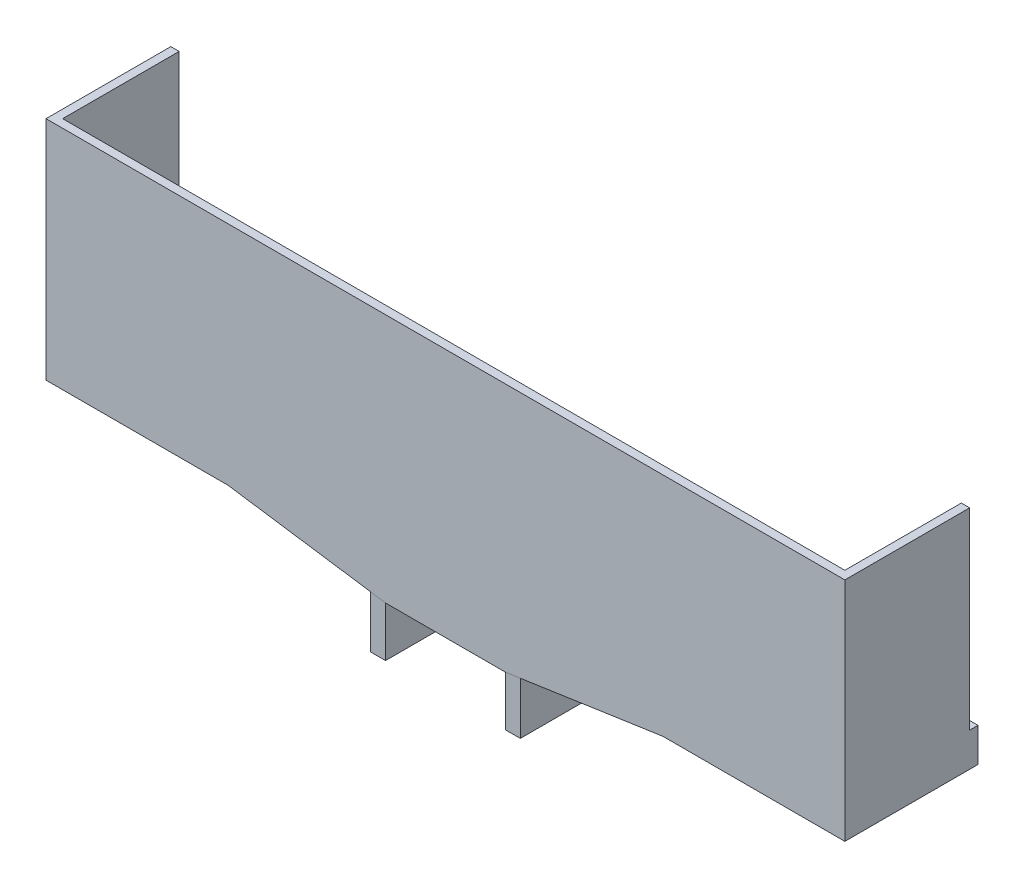
SolidWorks part; units mm, degrees
ref_plane "前基準面" through (0, 0, 0) normal (0, 0, 1) x (1, 0, 0)
ref_plane "上基準面" through (0, 0, 0) normal (0, 1, 0) x (1, 0, 0)
ref_plane "右基準面" through (0, 0, 0) normal (1, 0, 0) x (0, 0, -1)
sketch "草圖20" plane through (0, 0, 0) normal (0, 0, 1) x (1, 0, 0)
  line L0 (-36, 0) -> (36, 0) construction
  line L1 (-36, 0) -> (-240, 30)
  line L2 (-240, 30) -> (240, 30) construction
  line L3 (240, 30) -> (36, 0)
  line L4 (36, 0) -> (-36, 0)
  line L5 (0, 89.4424) -> (0, -40.7257) construction
  line L7 (-240, 30) -> (240, 30) construction
  line L8 (-240, 30) -> (-240, 150)
  line L9 (-240, 150) -> (240, 150)
  line L10 (240, 30) -> (240, 150)
  point P2 (0, 0)
  dimension "D1" = 72
  dimension "D2" = 480
  dimension "D3" = 30
  dimension "D4" = 120
extrude "填料-伸長1" add sketch "草圖20" along normal blind 80
ref_plane "平面1" through (0, 0, 5) normal (0, 0, 1) x (1, 0, 0)
sketch "草圖22" plane through (0, 0, 5) normal (0, 0, 1) x (1, 0, 0)
  line L6 (-235, 34.3185) -> (-35.6343, 5)
  line L7 (-235, 34.3185) -> (-36, 5.0538)
  line L8 (35.6343, 5) -> (235, 34.3185)
  line L9 (36, 5.0538) -> (235, 34.3185)
  line L332 (36, 0) -> (36, 5.0538)
  line L333 (-36, 0) -> (-36, 5.0538)
  line L334 (-36, 0) -> (36, 0) construction
  line L335 (-36, 0) -> (36, 0)
  line L336 (240, 150) -> (-240, 150) construction
  line L337 (235, 150) -> (-235, 150)
  line L338 (-35.6343, 5) -> (35.6343, 5)
  line L340 (-235, 145) -> (-235, 34.3185)
  line L341 (235, 145) -> (-235, 145)
  line L342 (235, 34.3185) -> (235, 145)
  line L346 (-235, 150) -> (-235, 34.3185)
  line L348 (235, 34.3185) -> (235, 150)
  dimension "D1" = 5
extrude "除料-伸長1" cut sketch "草圖22" along normal blind 70
sketch "草圖23" plane through (0, 0, 0) normal (0, 0, -1) x (-1, 0, 0)
  line L0 (-240, 34.3185) -> (-235, 34.3185)
  line L1 (-240, 150) -> (240, 150)
  line L2 (-240, 150) -> (-240, 34.3185)
  line L4 (240, 150) -> (240, 34.3185)
  line L5 (240, 150) -> (240, 30) construction
  line L6 (235, 34.3185) -> (36, 5.0538) construction
  line L7 (-36, 5.0538) -> (-235, 34.3185) construction
  line L8 (235, 34.3185) -> (36, 5.0538)
  line L9 (-36, 5.0538) -> (-235, 34.3185)
  line L10 (235, 34.3185) -> (240, 34.3185)
  line L15 (-36, 0) -> (36, 0)
  line L16 (-36, 5.0538) -> (-36, 0)
  line L17 (-235, 34.3185) -> (-36, 5.0538)
  line L18 (-235, 150) -> (-235, 34.3185)
  line L19 (235, 150) -> (-235, 150)
  line L20 (235, 34.3185) -> (235, 150)
  line L21 (36, 5.0538) -> (235, 34.3185)
  line L22 (36, 0) -> (36, 5.0538)
  line L23 (-36, 0) -> (36, 0)
  line L24 (-36, 5.0538) -> (-36, 0)
  line L25 (-235, 34.3185) -> (-36, 5.0538) construction
  line L26 (-235, 150) -> (-235, 34.3185) construction
  line L27 (235, 150) -> (-235, 150) construction
  line L28 (235, 34.3185) -> (235, 150) construction
  line L29 (36, 5.0538) -> (235, 34.3185) construction
  line L30 (36, 0) -> (36, 5.0538)
  dimension "D1" = 0
extrude "除料-伸長2" cut sketch "草圖23" against normal up to surface (5 mm away) up to face at (0, 47.3431, 5)
sketch "草圖25" plane through (0, 0, 0) normal (0, -1, 0) x (1, 0, 0)
  line L0 (-240, 80) -> (-36, 80) construction
  line L1 (-45, 80) -> (-36, 80)
  line L2 (-45, 80) -> (-45, 40)
  line L3 (-45, 40) -> (-36, 40)
  line L4 (45, 80) -> (45, 40)
  line L8 (-36, 75) -> (-36, 0) construction
  line L9 (-36, 75) -> (-36, 0)
  line L10 (36, 75) -> (36, 0) construction
  line L11 (36, 75) -> (36, 0)
  line L14 (0, 112.0403) -> (0, -32.5908) construction
  line L15 (-36, 80) -> (-36, 40)
  line L16 (36, 80) -> (45, 80)
  line L17 (36, 80) -> (36, 40)
  line L18 (36, 40) -> (45, 40)
  line M10 (-36, 80) -> (-36, 75)
  line M12 (36, 75) -> (36, 80)
  dimension "D1" = 90
  dimension "D2" = 40
extrude "填料-伸長3" add sketch "草圖25" along normal blind 30 and the other way up to next separate body contours L15 L9 L1 L2 L3 M10 | L17 L18 L4 L16 L11 M12
sketch "草圖26" plane through (0, 0, 0) normal (0, 0, -1) x (-1, 0, 0)
  line L0 (-130.69, 13.925) -> (-240, 13.925)
  line L1 (-36, 0) -> (-240, 30) construction
  line L2 (-240, 13.925) -> (-240, 30)
  line L3 (-240, 30) -> (-130.69, 13.925)
  line L5 (0, 209.7105) -> (0, -36.6515) construction
  line L6 (240, 13.925) -> (240, 30)
  line L7 (130.69, 13.925) -> (240, 13.925)
  line L8 (240, 30) -> (130.69, 13.925)
  dimension "D1" = 109.31
  dimension "D2" = 16.075
extrude "填料-伸長4" add sketch "草圖26" against normal up to surface (80 mm away) up to face at (0, 60, 80)
chamfer "導角1" distance 3 angle 45 2 edges at (-36, 5.0538, 37.5) (36, 5.0538, 37.5)
